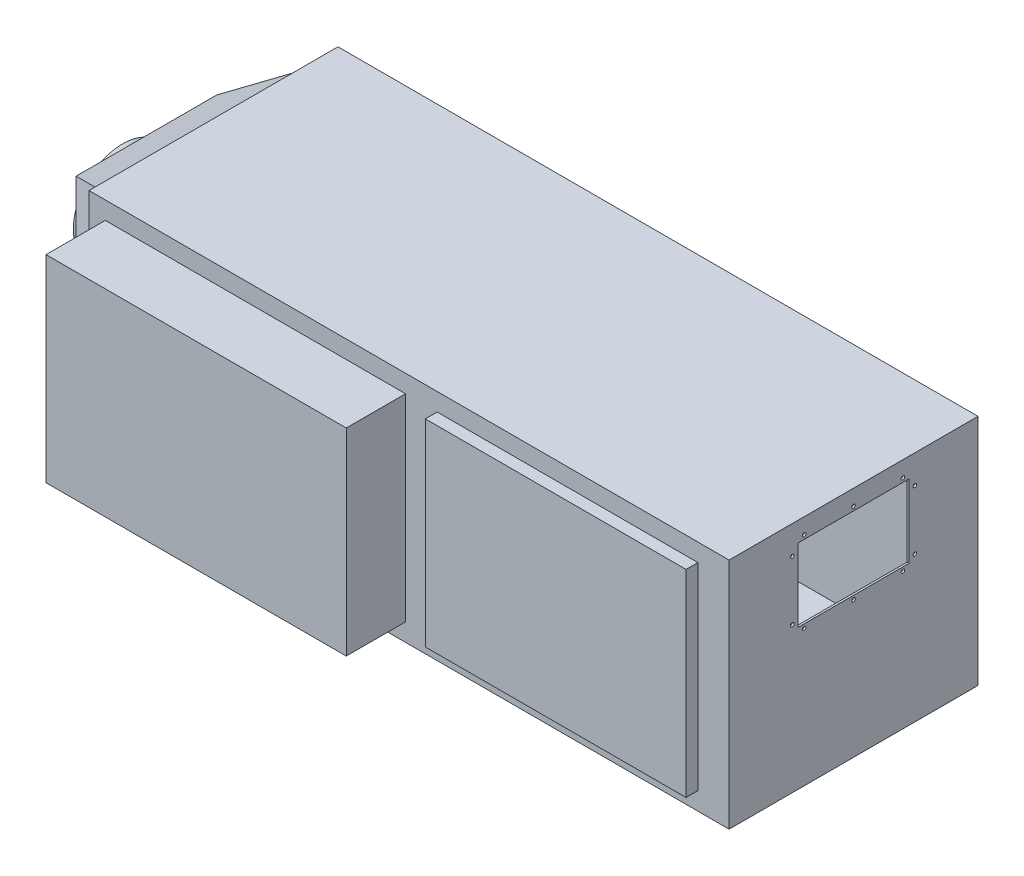
SolidWorks part; units mm, degrees
ref_plane "Front Plane" through (0, 0, 0) normal (0, 0, 1) x (1, 0, 0)
ref_plane "Top Plane" through (0, 0, 0) normal (0, 1, 0) x (1, 0, 0)
ref_plane "Right Plane" through (0, 0, 0) normal (1, 0, 0) x (0, 0, -1)
sketch "Sketch1" plane through (0, 0, 0) normal (0, 1, 0) x (1, 0, 0)
  line L1 (-810, 315) -> (810, 315)
  line L2 (-810, 315) -> (-810, -315)
  line L3 (-810, -315) -> (810, -315)
  line L4 (810, 315) -> (810, -315)
  line L5 (-810, 315) -> (810, -315) construction
  line L6 (-810, -315) -> (810, 315) construction
  point P0 (0, 0)
  dimension "D1" = 630
  dimension "D2" = 1620
extrude "Boss-Extrude1" add sketch "Sketch1" along normal blind 590
sketch "Sketch2" plane through (0, 0, 315) normal (0, 0, 1) x (1, 0, 0)
  line L0 (-810, 590) -> (810, 590) construction
  line L1 (-768.9264, 545) -> (-8.9264, 545)
  line L2 (-768.9264, 545) -> (-768.9264, 45)
  line L3 (-768.9264, 45) -> (-8.9264, 45)
  line L4 (-8.9264, 545) -> (-8.9264, 45)
  dimension "D1" = 760
  dimension "D2" = 500
  dimension "D3" = 45
extrude "Boss-Extrude2" add sketch "Sketch2" along normal blind 150 separate body
sketch "Sketch3" plane through (-810, 0, 0) normal (-1, 0, 0) x (0, 0, 1)
  line L0 (315, 590) -> (315, 0) construction
  line L1 (-280, 570) -> (280, 570)
  line L2 (-280, 570) -> (-280, 20)
  line L3 (-280, 20) -> (280, 20)
  line L4 (280, 570) -> (280, 20)
  line L5 (-315, 590) -> (315, 590) construction
  dimension "D1" = 560
  dimension "D2" = 35
  dimension "D3" = 550
  dimension "D4" = 20
extrude "Boss-Extrude3" add sketch "Sketch3" along normal blind 170 draft 31
sketch "Sketch4" plane through (-980, 0, 0) normal (-1, 0, 0) x (0, 0, 1)
  line L0 (-177.8537, 295) -> (0, 295) construction
  line L1 (-177.8537, 467.8537) -> (-177.8537, 122.1463) construction
  circle A0 centre (0, 295) radius 125
  dimension "D1" = 250
extrude "Boss-Extrude4" add sketch "Sketch4" along normal blind 60
sketch "Sketch5" plane through (0, 0, 315) normal (0, 0, 1) x (1, 0, 0)
  line L1 (71.0736, 545) -> (731.0736, 545)
  line L2 (71.0736, 545) -> (71.0736, 45)
  line L3 (71.0736, 45) -> (731.0736, 45)
  line L4 (731.0736, 545) -> (731.0736, 45)
  line L8 (-8.9264, 545) -> (-768.9264, 545) construction
  line L9 (-768.9264, 45) -> (-8.9264, 45) construction
  line L12 (-8.9264, 45) -> (-8.9264, 545) construction
  dimension "D1" = 660
  dimension "D2" = 80
extrude "Boss-Extrude5" add sketch "Sketch5" along normal blind 30
shell "Shell1" thickness 5
sketch "Sketch7" plane through (810, 0, 0) normal (1, 0, 0) x (0, 0, -1)
  line L0 (0, 5.7612) -> (0, 496.6297) construction
  line L1 (-140, 540.1784) -> (140, 540.1784)
  line L2 (-140, 540.1784) -> (-140, 355.1784)
  line L3 (-140, 355.1784) -> (140, 355.1784)
  line L4 (140, 540.1784) -> (140, 355.1784)
  line L5 (-140, 540.1784) -> (140, 355.1784) construction
  line L6 (-140, 355.1784) -> (140, 540.1784) construction
  line L7 (-125, 550.1784) -> (0, 550.1784) construction
  line L8 (-155, 518.1784) -> (155, 518.1784) construction
  circle A0 centre (-125, 550.1784) radius 4.5
  circle A1 centre (0, 550.1784) radius 4.5
  circle A2 centre (125, 550.1784) radius 4.5
  circle A3 centre (0, 345.1784) radius 4.5
  circle A4 centre (125, 345.1784) radius 4.5
  circle A5 centre (-125, 345.1784) radius 4.5
  circle A6 centre (-155, 518.1784) radius 4.5
  circle A7 centre (155, 518.1784) radius 4.5
  circle A8 centre (155, 368.1784) radius 4.5
  circle A9 centre (-155, 368.1784) radius 4.5
  point P0 (0, 447.6784)
  dimension "D3" = 9
  dimension "D5" = 10
  dimension "D9" = 22
  dimension "D1" = 280
  dimension "D2" = 185
  dimension "D4" = 15
  dimension "D8" = 125
  dimension "D10" = 15
  dimension "D11" = 2
  dimension "D13" = 310
  dimension "D6" = 3
  dimension "D7" = 2
  dimension "D12" = 2
extrude "Cut-Extrude1" cut sketch "Sketch7" against normal blind 10
scale "Scale1" bodies to scale 102 114 scale about origin uniform scaling yes scale factor 0.1
